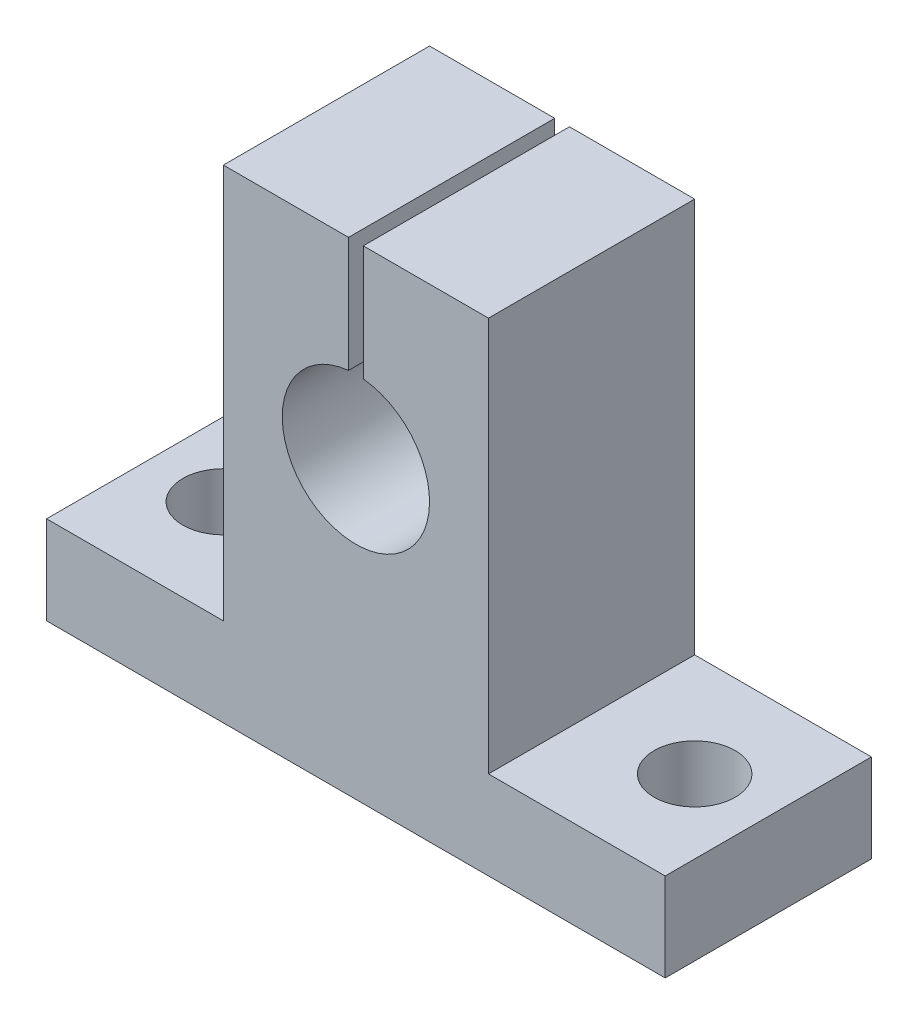
SolidWorks part; units mm, degrees
ref_plane "前视基准面" through (0, 0, 0) normal (0, 0, 1) x (1, 0, 0)
ref_plane "上视基准面" through (0, 0, 0) normal (0, 1, 0) x (1, 0, 0)
ref_plane "右视基准面" through (0, 0, 0) normal (1, 0, 0) x (0, 0, -1)
sketch "草图4" plane through (0, 0, 0) normal (0, 0, 1) x (1, 0, 0)
  line L0 (0, -20) -> (0, 0) construction
  line L1 (-21, -20) -> (-21, -14)
  line L2 (-21, -14) -> (-9, -14)
  line L3 (-21, -20) -> (21, -20)
  line L4 (-9, -14) -> (-9, 12.8)
  line L5 (-9, 12.8) -> (9, 12.8)
  line L6 (9, 12.8) -> (9, -14)
  line L7 (9, -14) -> (21, -14)
  line L8 (21, -14) -> (21, -20)
  line L9 (0, 0) -> (0, 13.6669) construction
  line L10 (-0.5, 13.6669) -> (0.5, 13.6669)
  line L11 (-0.5, 13.6669) -> (-0.5, 4.519)
  line L12 (-0.5, 4.519) -> (0.5, 4.519)
  line L13 (0.5, 4.519) -> (0.5, 13.6669)
  circle A0 centre (0, 0) radius 5
  point P14 (0, -20)
  point P15 (0, -20)
  dimension "D1" = 10
  dimension "D2" = 20
  dimension "D3" = 6
  dimension "D4" = 42
  dimension "D5" = 32.8
  dimension "D6" = 18
  dimension "D7" = 1
extrude "凸台-拉伸3" add sketch "草图4" along normal blind 14 contours A0 L11 L5 L4 L2 L1 L3 L8 L7 L6 L13
sketch "草图5" plane through (0, -14, 0) normal (0, 1, 0) x (1, 0, 0)
  line L0 (-9, -7) -> (-16, -7) construction
  line L1 (-9, -14) -> (-9, 0) construction
  line L2 (-21, -14) -> (-21, 0) construction
  line L4 (16, -7) -> (9, -7) construction
  line L5 (9, -14) -> (9, 0) construction
  circle A0 centre (-16, -7) radius 2.75
  circle A1 centre (16, -7) radius 2.75
  dimension "D1" = 5.5
  dimension "D2" = 32
  dimension "D3" = 5
extrude "切除-拉伸1" cut sketch "草图5" against normal through all
